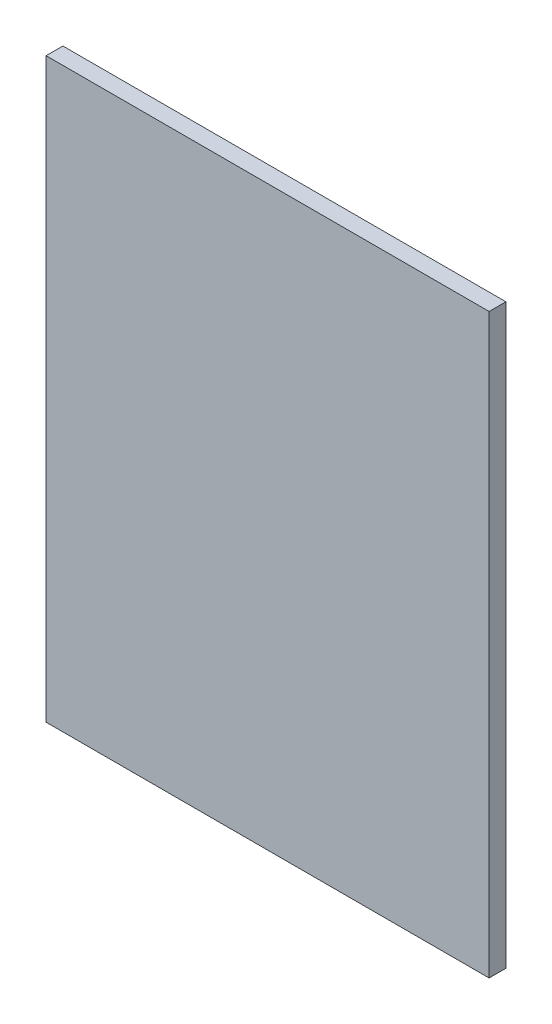
SolidWorks part; units mm, degrees
ref_plane "Front Plane" through (0, 0, 0) normal (0, 0, 1) x (1, 0, 0)
ref_plane "Top Plane" through (0, 0, 0) normal (0, 1, 0) x (1, 0, 0)
ref_plane "Right Plane" through (0, 0, 0) normal (1, 0, 0) x (0, 0, -1)
sketch "Sketch1" plane through (0, 0, 0) normal (0, 0, 1) x (1, 0, 0)
  line L1 (-40.3225, -56.1975) -> (40.3225, -56.1975)
  line L2 (-40.3225, -56.1975) -> (-40.3225, 56.1975)
  line L3 (-40.3225, 56.1975) -> (40.3225, 56.1975)
  line L4 (40.3225, -56.1975) -> (40.3225, 56.1975)
  line L5 (-40.3225, -56.1975) -> (40.3225, 56.1975) construction
  line L6 (-40.3225, 56.1975) -> (40.3225, -56.1975) construction
extrude "Boss-Extrude1" add sketch "Sketch1" along normal blind 3.175
sketch "Sketch2" plane through (40.3225, 0, 0) normal (1, 0, 0) x (0, 0, -1)
  line L1 (0, 56.1975) -> (-3.175, 56.1975)
  line L2 (0, 56.1975) -> (0, -56.1975)
  line L3 (0, -56.1975) -> (-3.175, -56.1975)
  line L4 (-3.175, 56.1975) -> (-3.175, -56.1975)
extrude "Boss-Extrude2" add sketch "Sketch2" along normal blind 3.175
sketch "Sketch3" plane through (0, 56.1975, 0) normal (0, 1, 0) x (-1, 0, 0)
  line L1 (-43.4975, 0) -> (40.3225, 0)
  line L2 (-43.4975, 0) -> (-43.4975, 3.175)
  line L3 (-43.4975, 3.175) -> (40.3225, 3.175)
  line L4 (40.3225, 0) -> (40.3225, 3.175)
extrude "Cut-Extrude1" cut sketch "Sketch3" against normal blind 3.175
